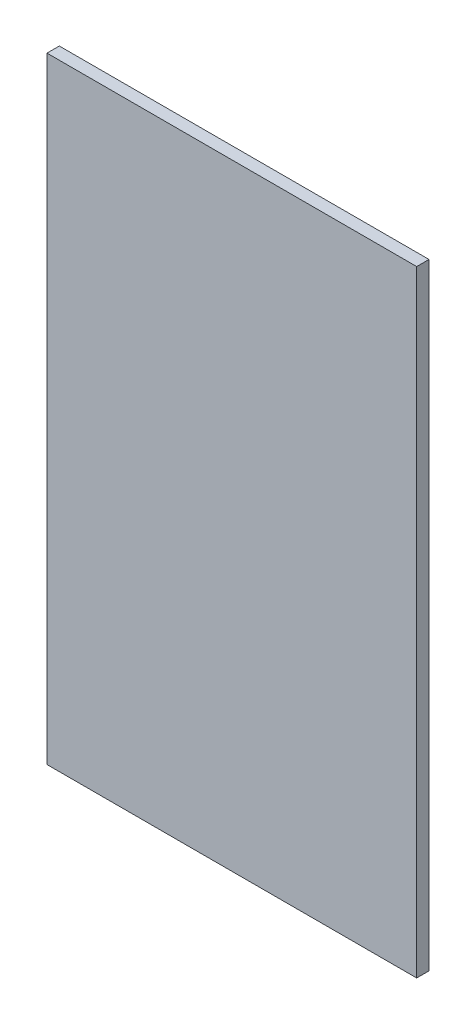
SolidWorks part; units mm, degrees
ref_plane "Plan de face" through (0, 0, 0) normal (0, 0, 1) x (1, 0, 0)
ref_plane "Plan de dessus" through (0, 0, 0) normal (0, 1, 0) x (1, 0, 0)
ref_plane "Plan de droite" through (0, 0, 0) normal (1, 0, 0) x (0, 0, -1)
sketch "Esquisse1" plane through (0, 0, 0) normal (0, 0, 1) x (1, 0, 0)
  line L0 (115.6323, 16.4322) -> (115.6323, -87.4226) construction
  line L1 (-24.3677, -96.2679) -> (125.6323, -96.2679)
  line L2 (-24.3677, -96.2679) -> (-24.3677, 153.7321)
  line L3 (-24.3677, 153.7321) -> (125.6323, 153.7321)
  line L4 (125.6323, -96.2679) -> (125.6323, 153.7321)
  line L6 (95.6646, -95.2679) -> (107.6646, -95.2679) construction
  dimension "D1" = 150
  dimension "D2" = 10
  dimension "D3" = 250
  dimension "D4" = 1
extrude "Boss.-Extru.1" add sketch "Esquisse1" along normal blind 5
